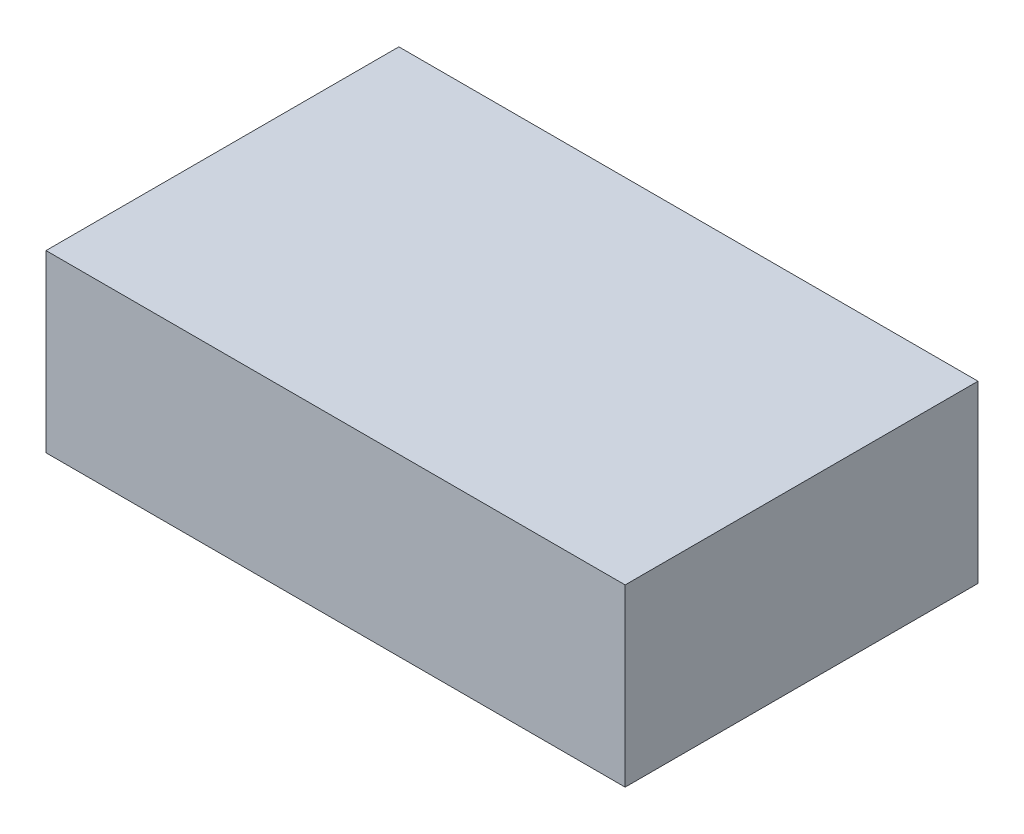
SolidWorks part; units mm, degrees
material "Pine"
ref_plane "Front Plane" through (0, 0, 0) normal (0, 0, 1) x (1, 0, 0)
ref_plane "Top Plane" through (0, 0, 0) normal (0, 1, 0) x (1, 0, 0)
ref_plane "Right Plane" through (0, 0, 0) normal (1, 0, 0) x (0, 0, -1)
sketch "Sketch1" plane through (0, 0, 0) normal (0, 1, 0) x (1, 0, 0)
  line L1 (-41.9899, 25.584) -> (41.9899, 25.584)
  line L2 (-41.9899, 25.584) -> (-41.9899, -25.584)
  line L3 (-41.9899, -25.584) -> (41.9899, -25.584)
  line L4 (41.9899, 25.584) -> (41.9899, -25.584)
  line L5 (-41.9899, 25.584) -> (41.9899, -25.584) construction
  line L6 (-41.9899, -25.584) -> (41.9899, 25.584) construction
  point P0 (0, 0)
extrude "Boss-Extrude1" add sketch "Sketch1" along normal blind 25.4
